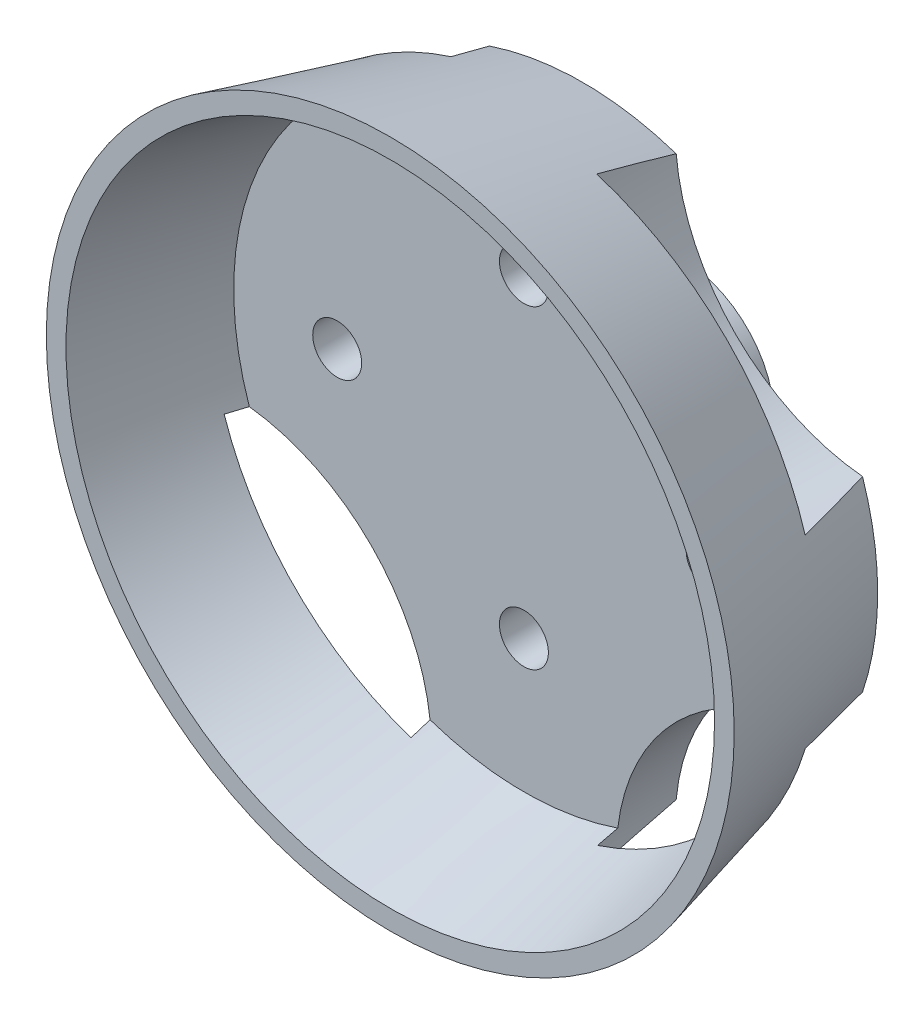
SolidWorks part; units mm, degrees
ref_plane "Спереди" through (0, 0, 0) normal (0, 0, 1) x (1, 0, 0)
ref_plane "Сверху" through (0, 0, 0) normal (0, 1, 0) x (1, 0, 0)
ref_plane "Справа" through (0, 0, 0) normal (1, 0, 0) x (0, 0, -1)
sketch "Эскиз1" plane through (0, 0, 0) normal (1, 0, 0) x (0, 0, -1)
  line L0 (0, 0) -> (8, 0)
  line L1 (8, 0) -> (8, 4.75)
  line L2 (8, 4.75) -> (3, 4.75)
  line L3 (3, 4.75) -> (3, 15)
  line L4 (3, 15) -> (-6.8, 17.5)
  line L5 (-6.8, 17.5) -> (-6.8, 16.5)
  line L6 (-6.8, 16.5) -> (0, 14.7653)
  line L7 (0, 14.7653) -> (0, 0)
  dimension "D1" = 15
  dimension "D2" = 4.75
  dimension "D3" = 5
  dimension "D4" = 3
  dimension "D5" = 9.8
  dimension "D6" = 16.5
  dimension "D7" = 17.5
revolve "Повернуть1" add sketch "Эскиз1" angle 360 about L0
sketch "Эскиз2" plane through (0, 0, -3) normal (0, 0, -1) x (-1, 0, 0)
  line L0 (-15.2028, -15.2028) -> (0, 0) construction
  line L1 (0, -8) -> (0, 0) construction
  circle A0 centre (0, 8) radius 1.245
  circle A1 centre (0, -8) radius 1.245
  circle A2 centre (9.5, 0) radius 1.245
  circle A3 centre (-9.5, 0) radius 1.245
  circle A4 centre (0, 0) radius 9.5 construction
  circle A5 centre (0, 0) radius 8 construction
  circle A6 centre (0, 0) radius 21.5 construction
  circle A7 centre (-15.2028, -15.2028) radius 10.5
  circle A8 centre (-15.2028, 15.2028) radius 10.5
  circle A9 centre (15.2028, 15.2028) radius 10.5 [skipped]
  circle A10 centre (15.2028, -15.2028) radius 10.5
  point P24 (0, 0)
  dimension "D1" = 2.49
  dimension "D2" = 16
  dimension "D3" = 19
  dimension "D4" = 21
  dimension "D5" = 43
  dimension "D6" = 45
  dimension "D7" = 4
extrude "Вырез-Вытянуть1" cut sketch "Эскиз2" against normal blind 4
sketch "Эскиз3" plane through (0, 0, -3) normal (0, 0, -1) x (-1, 0, 0)
  line L0 (15.2028, 15.2028) -> (0, 0) construction
  circle A0 centre (0, 0) radius 21.5 construction
  circle A1 centre (15.2028, 15.2028) radius 10.5
  arc A2 (-14.2287, 4.7481) -> (-4.7481, 14.2287) centre (-15.2028, 15.2028) ccw construction
  arc A3 (14.2287, -4.7481) -> (4.7481, -14.2287) centre (15.2028, -15.2028) ccw construction
  dimension "D1" = 43
  dimension "D2" = 21
extrude "Вырез-Вытянуть2" cut sketch "Эскиз3" against normal blind 2
